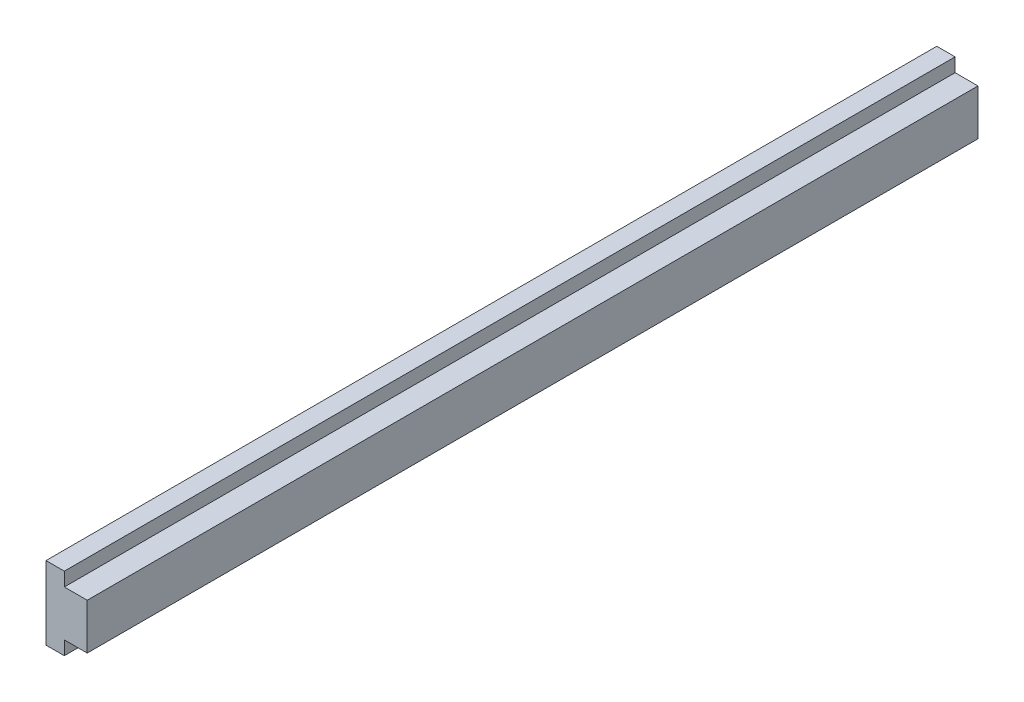
SolidWorks part; units mm, degrees
ref_plane "Front Plane" through (0, 0, 0) normal (1, 0, 0) x (0, 1, 0)
ref_plane "Top Plane" through (0, 0, 0) normal (0, 0, 1) x (0, 1, 0)
ref_plane "Right Plane" through (0, 0, 0) normal (0, 1, 0) x (-1, 0, 0)
sketch "Sketch1" plane through (0, 0, 0) normal (0, 0, 1) x (0, 1, 0)
  line L1 (-8, -2) -> (8, -2)
  line L2 (-8, -2) -> (-8, 2)
  line L3 (-8, 2) -> (8, 2)
  line L4 (8, -2) -> (8, 2)
  line L5 (-8, -2) -> (8, 2) construction
  line L6 (-8, 2) -> (8, -2) construction
  line L7 (-5, -2) -> (5, -2)
  line L8 (-5, -2) -> (-5, -7)
  line L9 (-5, -7) -> (5, -7)
  line L10 (5, -2) -> (5, -7)
  point P0 (0, 0)
  dimension "D1" = 9
  dimension "D2" = 4
  dimension "D3" = 16
  dimension "D4" = 10
  dimension "D5" = 3
extrude "Boss-Extrude1" add sketch "Sketch1" against normal blind 194.5 contours L10 L1 L8 L9 | L1 L4 L3 L2
sketch "Sketch2" plane through (0, 0, -194.5) normal (0, 0, -1) x (1, 0, 0)
  line L0 (0, 0) -> (2.5, 0) construction
  line L1 (-0.55, -3.05) -> (5.55, -3.05)
  line L2 (-0.55, -3.05) -> (-0.55, 3.05)
  line L3 (-0.55, 3.05) -> (5.55, 3.05)
  line L4 (5.55, -3.05) -> (5.55, 3.05)
  line L5 (-0.55, -3.05) -> (5.55, 3.05) construction
  line L6 (-0.55, 3.05) -> (5.55, -3.05) construction
  line L7 (-2, 8) -> (-2, -8) construction
  point P0 (2.5, 0)
  dimension "D1" = 6.1
  dimension "D2" = 6.1
  dimension "D3" = 4.5
extrude "Cut-Extrude1" cut sketch "Sketch2" against normal blind 20
equation "\"CD_Height\"= 125mm"
equation "\"CD_Thickness\"= 10mm"
equation "\"CD_Width\"= 142mm"
equation "\"Wall_Thickness\"= 10mm"
equation "\"Total_Height\"= 3 * \"CD_Height\" + 2 * \"Wall_Thickness\" + 4mm"
equation "\"Total_Width\"= \"CD_Width\" * 3 + \"Wall_Thickness\" * 2 + 4mm"
equation "\"Tolerance\"= 1mm"
equation "\"Overhang_Width\"= 10mm"
equation "\"D1@Sketch1\"=\"Wall_Thickness\"-1mm"
equation "\"D2@Sketch1\"=\"Wall_Thickness\"/2-1mm"
equation "\"D3@Sketch1\"=\"Wall_Thickness\"+6mm"
equation "\"D4@Sketch1\"=\"Wall_Thickness\""
equation "\"D1@Boss-Extrude1\"=(\"Total_Height\"-\"Wall_Thickness\")/2"
equation "\"D1@Sketch2\"=\"Wall_Thickness\"-4mm+0.1mm"
equation "\"D2@Sketch2\"=\"Wall_Thickness\"-4mm+0.1mm"
equation "\"D3@Sketch2\"=(\"Wall_Thickness\"-1)/2"
